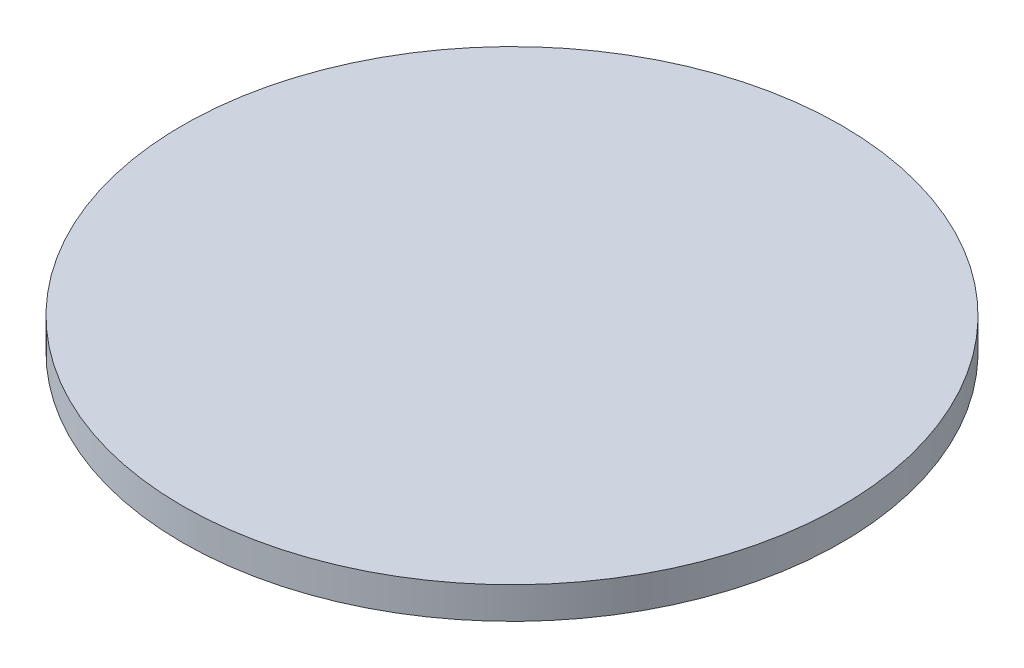
SolidWorks part; units mm, degrees
ref_plane "Front Plane" through (0, 0, 0) normal (0, 0, 1) x (1, 0, 0)
ref_plane "Top Plane" through (0, 0, 0) normal (0, 1, 0) x (1, 0, 0)
ref_plane "Right Plane" through (0, 0, 0) normal (1, 0, 0) x (0, 0, -1)
sketch "Sketch1" plane through (0, 0, 0) normal (0, 1, 0) x (1, 0, 0)
  circle A0 centre (0, 0) radius 10.375
  dimension "D1" = 20.75
extrude "Boss-Extrude1" add sketch "Sketch1" along normal blind 1
